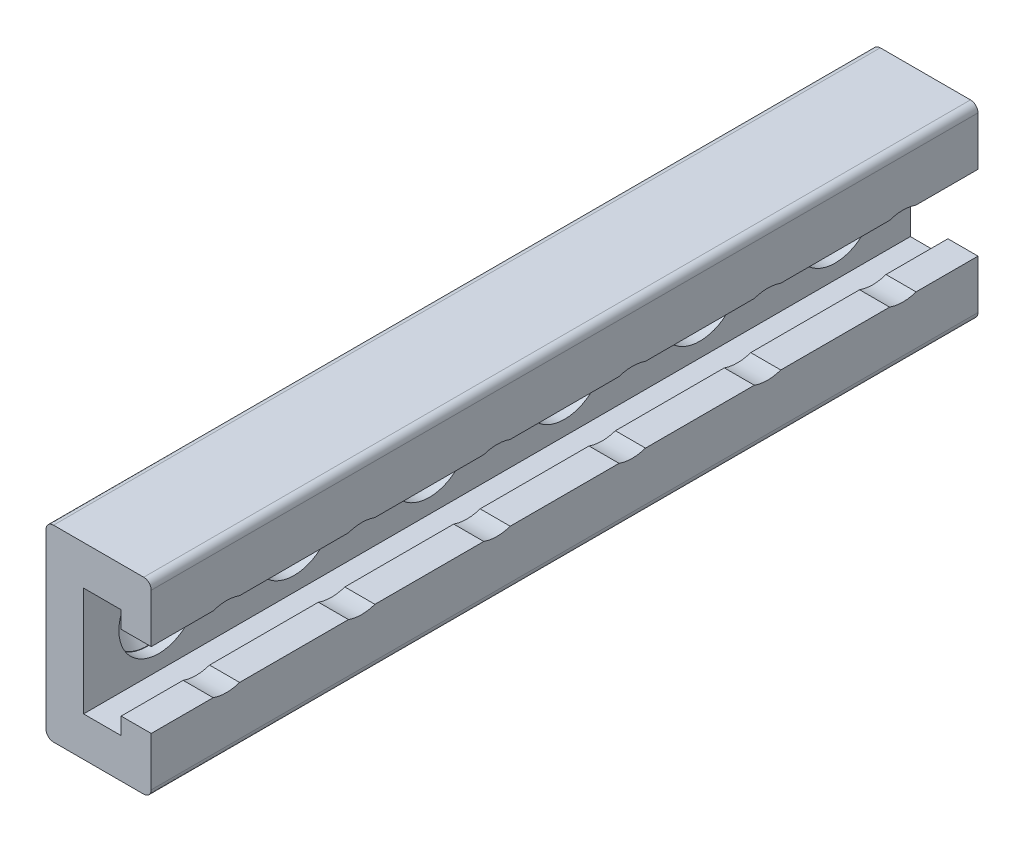
SolidWorks part; units mm, degrees
ref_plane "前视基准面" through (0, 0, 0) normal (0, 0, 1) x (1, 0, 0)
ref_plane "上视基准面" through (0, 0, 0) normal (0, 1, 0) x (1, 0, 0)
ref_plane "右视基准面" through (0, 0, 0) normal (1, 0, 0) x (0, 0, -1)
sketch "草图1" plane through (0, 0, 0) normal (0, 0, 1) x (1, 0, 0)
  line L48 (1315.3371, 1002.714) -> (1315.3371, 1025.714)
  line L49 (1325.3371, 1009.214) -> (1329.3371, 1009.214)
  line L50 (1325.3371, 1019.214) -> (1329.3371, 1019.214)
  line L51 (1320.3371, 1006.964) -> (1320.3371, 1021.464)
  line L52 (1320.3371, 1021.464) -> (1325.3371, 1021.464)
  line L53 (1320.3371, 1006.964) -> (1325.3371, 1006.964)
  line L54 (1325.3371, 1006.964) -> (1325.3371, 1009.214)
  line L55 (1329.3371, 1002.714) -> (1329.3371, 1009.214)
  line L56 (1329.3371, 1019.214) -> (1329.3371, 1025.714)
  line L57 (1325.3371, 1019.214) -> (1325.3371, 1021.464)
  line L58 (1316.3371, 1001.714) -> (1328.3371, 1001.714)
  line L59 (1316.3371, 1026.714) -> (1328.3371, 1026.714)
  line L60 (1311.5682, 1014.214) -> (1333.4053, 1014.214) construction
  arc A4 (1315.3371, 1002.714) -> (1316.3371, 1001.714) centre (1316.3371, 1002.714) ccw
  arc A5 (1316.3371, 1026.714) -> (1315.3371, 1025.714) centre (1316.3371, 1025.714) ccw
  arc A6 (1329.3371, 1025.714) -> (1328.3371, 1026.714) centre (1328.3371, 1025.714) ccw
  arc A7 (1328.3371, 1001.714) -> (1329.3371, 1002.714) centre (1328.3371, 1002.714) ccw
extrude "拉伸1" add sketch "草图1" along normal blind 110
sketch "草图2" plane through (1315.3371, 0, 0) normal (-1, 0, 0) x (0, 0, 1)
  line L0 (0, 1014.214) -> (115.4148, 1014.214) construction
  line L1 (0, 1025.714) -> (0, 1002.714) construction
  line L2 (110, 1025.714) -> (110, 1002.714) construction
  circle A0 centre (100, 1014.214) radius 2.75
  circle A1 centre (82, 1014.214) radius 2.75
  circle A2 centre (64, 1014.214) radius 2.75
  circle A3 centre (46, 1014.214) radius 2.75
  circle A4 centre (28, 1014.214) radius 2.75
  circle A5 centre (10, 1014.214) radius 2.75
  dimension "D1" = 5.5
  dimension "D2" = 10
extrude "拉伸2" cut sketch "草图2" against normal blind 110
sketch "草图3" plane through (1329.3371, 0, 0) normal (1, 0, 0) x (0, 0, -1)
  circle A0 centre (-100, 1014.214) radius 5.3
  circle A1 centre (-82, 1014.214) radius 5.3
  circle A2 centre (-64, 1014.214) radius 5.3
  circle A3 centre (-46, 1014.214) radius 5.3
  circle A4 centre (-28, 1014.214) radius 5.3
  circle A5 centre (-10, 1014.214) radius 5.3
  dimension "D1" = 10.6
extrude "拉伸3" cut sketch "草图3" against normal blind 10.6
chamfer "倒角1" distance 2.5 angle 45 1 edges at (1318.7371, 1014.214, 97.25)
chamfer "倒角2" distance 2.5 angle 45 1 edges at (1318.7371, 1014.214, 79.25)
chamfer "倒角3" distance 2.5 angle 45 1 edges at (1318.7371, 1014.214, 61.25)
chamfer "倒角4" distance 2.5 angle 45 1 edges at (1318.7371, 1014.214, 43.25)
chamfer "倒角5" distance 2.5 angle 45 1 edges at (1318.7371, 1014.214, 25.25)
chamfer "倒角6" distance 2.5 angle 45 1 edges at (1318.7371, 1014.214, 7.25)
